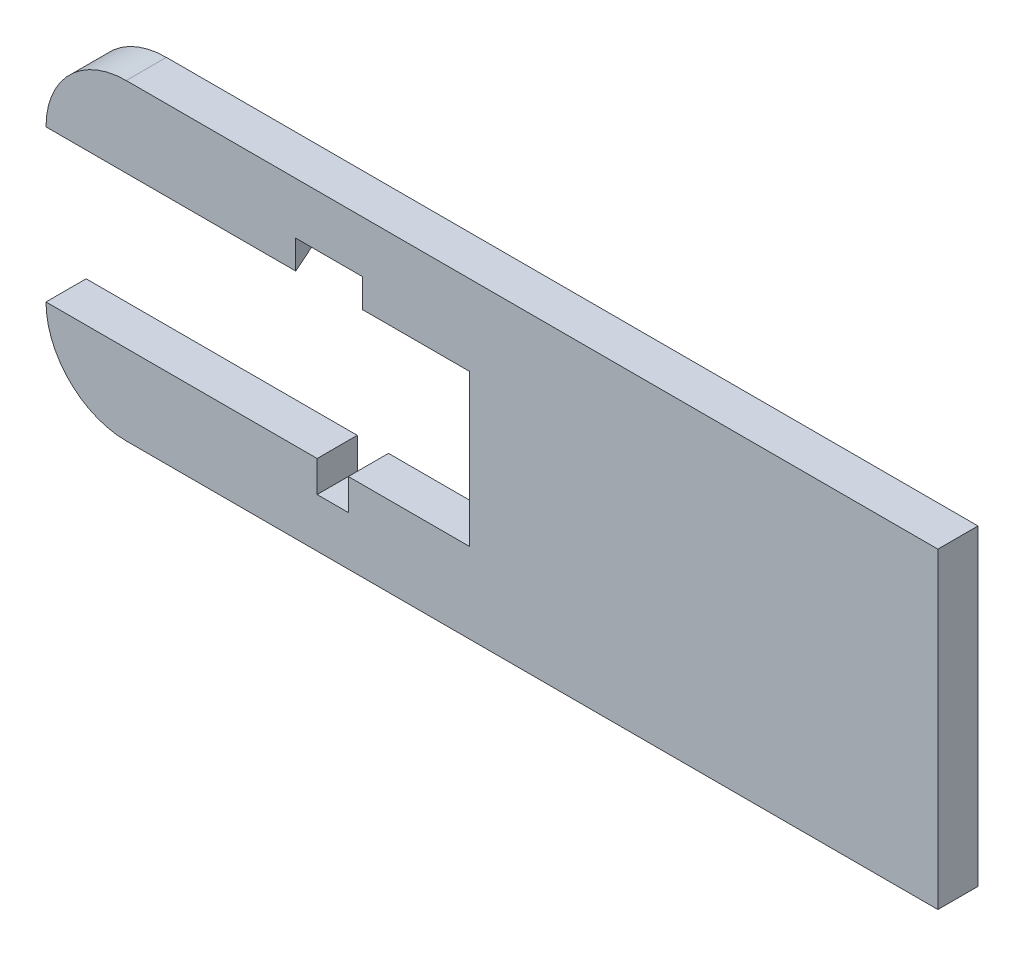
SolidWorks part; units mm, degrees
ref_plane "Front Plane" through (0, 0, 0) normal (0, 0, 1) x (1, 0, 0)
ref_plane "Top Plane" through (0, 0, 0) normal (0, 1, 0) x (1, 0, 0)
ref_plane "Right Plane" through (0, 0, 0) normal (1, 0, 0) x (0, 0, -1)
sketch "Sketch1" plane through (0, 0, 0) normal (0, 0, 1) x (1, 0, 0)
  line L1 (0, 0) -> (254, 0)
  line L2 (0, 0) -> (0, 88.9)
  line L3 (0, 88.9) -> (254, 88.9)
  line L4 (254, 0) -> (254, 88.9)
  dimension "D1" = 88.9
  dimension "D2" = 254
extrude "Boss-Extrude1" add sketch "Sketch1" along normal blind 11.43
fillet "Fillet1" radius 22.86 1 edges at (0, 88.9, 5.715)
fillet "Fillet2" radius 22.86 1 edges at (0, 0, 5.715)
sketch "Sketch2" plane through (0, 0, 0) normal (-1, 0, 0) x (0, 0, 1)
  line L1 (0, 22.86) -> (11.43, 22.86)
  line L2 (0, 22.86) -> (0, 66.04)
  line L3 (0, 66.04) -> (11.43, 66.04)
  line L4 (11.43, 22.86) -> (11.43, 66.04)
extrude "Cut-Extrude1" cut sketch "Sketch2" against normal blind 120.65
sketch "Sketch3" plane through (0, 0, 11.43) normal (0, 0, 1) x (1, 0, 0)
  line L0 (120.65, 22.86) -> (0, 22.86) construction
  line L1 (77.216, 22.86) -> (86.106, 22.86)
  line L2 (77.216, 22.86) -> (77.216, 13.97)
  line L3 (77.216, 13.97) -> (86.106, 13.97)
  line L4 (86.106, 22.86) -> (86.106, 13.97)
  dimension "D1" = 77.216
  dimension "D2" = 8.89
  dimension "D3" = 8.89
extrude "Cut-Extrude2" cut sketch "Sketch3" against normal up to surface (11.43 mm away) up to face at (98.1939, 44.45, 0)
sketch "Sketch4" plane through (0, 0, 11.43) normal (0, 0, 1) x (1, 0, 0)
  line L0 (120.65, 66.04) -> (0, 66.04) construction
  line L1 (71.12, 66.04) -> (90.17, 66.04)
  line L2 (71.12, 66.04) -> (71.12, 74.168)
  line L3 (71.12, 74.168) -> (90.17, 74.168)
  line L4 (90.17, 66.04) -> (90.17, 74.168)
  dimension "D1" = 19.05
  dimension "D2" = 8.128
  dimension "D3" = 71.12
extrude "Cut-Extrude3" cut sketch "Sketch4" against normal up to surface (11.43 mm away) up to face at (92.6829, 35.7717, 0)
sketch "Sketch5" plane through (0, 0, 0) normal (0, 0, -1) x (-1, 0, 0)
  line L0 (-71.12, 66.04) -> (0, 66.04) construction
  line L1 (-71.12, 74.168) -> (-66.04, 74.168)
  line L2 (-71.12, 74.168) -> (-71.12, 66.04)
  line L3 (-71.12, 66.04) -> (-66.04, 66.04)
  line L4 (-66.04, 74.168) -> (-66.04, 66.04)
  point P7 (-66.04, 74.168)
  dimension "D1" = 5.08
sketch "Sketch6" plane through (0, 66.04, 0) normal (0, -1, 0) x (1, 0, 0)
  line L0 (66.04, 0) -> (71.12, 11.43)
  line L1 (71.12, 11.43) -> (71.12, 0)
  line L2 (71.12, 0) -> (66.04, 0)
extrude "Cut-Extrude4" cut sketch "Sketch6" against normal up to vertex (8.128 mm away) up to point (66.04, 74.168, 0)
